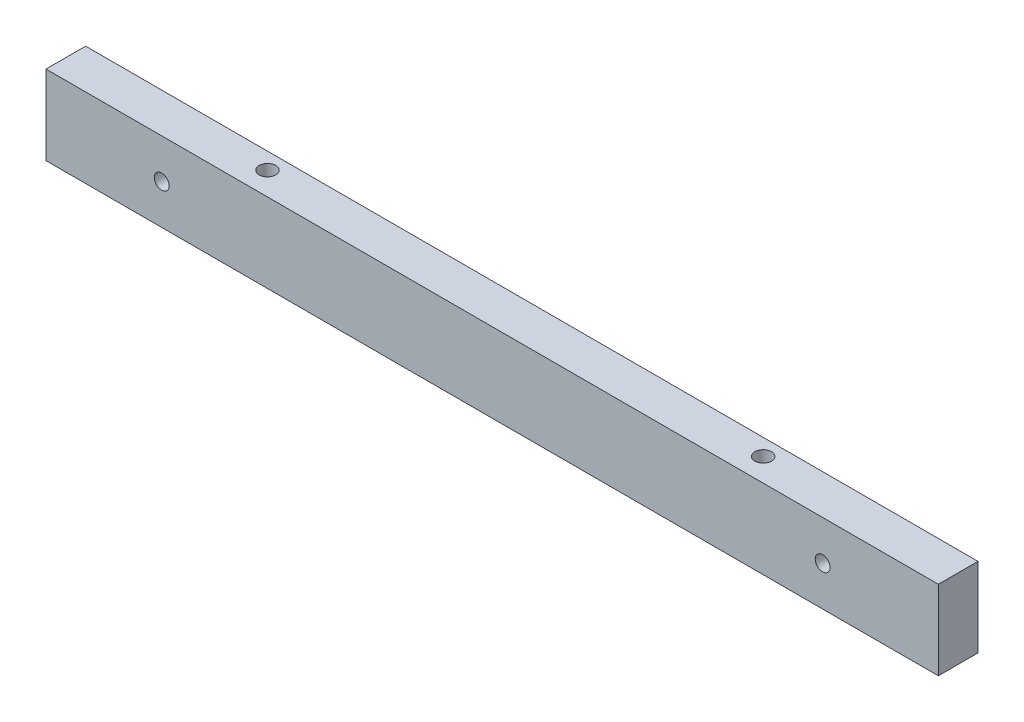
SolidWorks part; units mm, degrees
material "Sapin"
ref_plane "Plan de face" through (0, 0, 0) normal (0, 0, 1) x (1, 0, 0)
ref_plane "Plan de dessus" through (0, 0, 0) normal (0, 1, 0) x (1, 0, 0)
ref_plane "Plan de droite" through (0, 0, 0) normal (1, 0, 0) x (0, 0, -1)
sketch "Esquisse1" plane through (0, 0, 0) normal (0, 0, 1) x (1, 0, 0)
  line L0 (-319.5, -24) -> (319.5, -24)
  line L1 (319.5, -24) -> (319.5, 24)
  line L2 (319.5, 24) -> (-319.5, 24)
  line L3 (-319.5, 24) -> (-319.5, -24)
  line L4 (319.5, -24) -> (-319.5, 24) construction
  dimension "D1" = 639
  dimension "D2" = 48
extrude "Boss.-Extru.1" add sketch "Esquisse1" along normal blind 24
sketch "Esquisse2" plane through (0, 0, 24) normal (0, 0, 1) x (1, 0, 0)
  line L0 (-319.5, 24) -> (-271.5, -24)
  line L1 (-319.5, -24) -> (319.5, -24) construction
  line L2 (-271.5, -24) -> (-319.5, -24)
  line L3 (-319.5, -24) -> (-319.5, 24)
  line L4 (319.5, 24) -> (271.5, -24)
  line L5 (271.5, -24) -> (319.5, -24)
  line L6 (319.5, -24) -> (319.5, 24)
extrude "Enlèv. mat.-Extru.1" cut sketch "Esquisse2" against normal through all
sketch "Esquisse3" plane through (0, 0, 24) normal (0, 0, 1) x (1, 0, 0)
  line L0 (-271.5, -24) -> (271.5, -24) construction
  line L2 (0, 24) -> (0, -24) construction
  line L3 (319.5, 24) -> (-319.5, 24) construction
  circle A0 centre (-200, 0) radius 4.5
  circle A1 centre (200, 0) radius 4.5
  dimension "D3" = 9
  dimension "D2" = 400
extrude "Enlèv. mat.-Extru.2" cut sketch "Esquisse3" against normal through all
sketch "Esquisse4" [suppressed] plane through (0, 0, 24) normal (0, 0, 1) x (1, 0, 0)
  circle A0 centre (119.5, 24) radius 10
  circle A1 centre (519.5, 24) radius 10
  dimension "D1" = 20
extrude "Enlèv. mat.-Extru.3" [suppressed] cut sketch "Esquisse4" against normal blind 10
sketch "Esquisse5" plane through (0, 24, 0) normal (0, 1, 0) x (1, 0, 0)
  line L0 (0, -10) -> (639, -10) construction
  line L3 (0, 0) -> (0, -24) construction
  line L4 (319.5, 0) -> (-319.5, 0) construction
  line L5 (319.5, -24) -> (-319.5, -24) construction
  circle A0 centre (-150, -10) radius 5
  circle A1 centre (150, -10) radius 5
  dimension "D2" = 10
  dimension "D1" = 300
  dimension "D3" = 14
extrude "Enlèv. mat.-Extru.4" cut sketch "Esquisse5" against normal through all
sketch "Esquisse6" plane through (0, 0, 0) normal (0, 0, -1) x (-1, 0, 0)
  line L0 (-270, -25.5) -> (-270, 24)
  line L1 (-319.5, 24) -> (319.5, 24) construction
  line L2 (-270, 24) -> (-319.5, 24)
  line L3 (-319.5, 24) -> (-270, -25.5)
  line L4 (270, -25.5) -> (319.5, 24)
  line L5 (319.5, 24) -> (270, 24)
  line L6 (270, 24) -> (270, -25.5)
  line L7 (0, 0) -> (0, 56.9443) construction
  dimension "D1" = 540
extrude "Enlèv. mat.-Extru.5" cut sketch "Esquisse6" against normal through all
